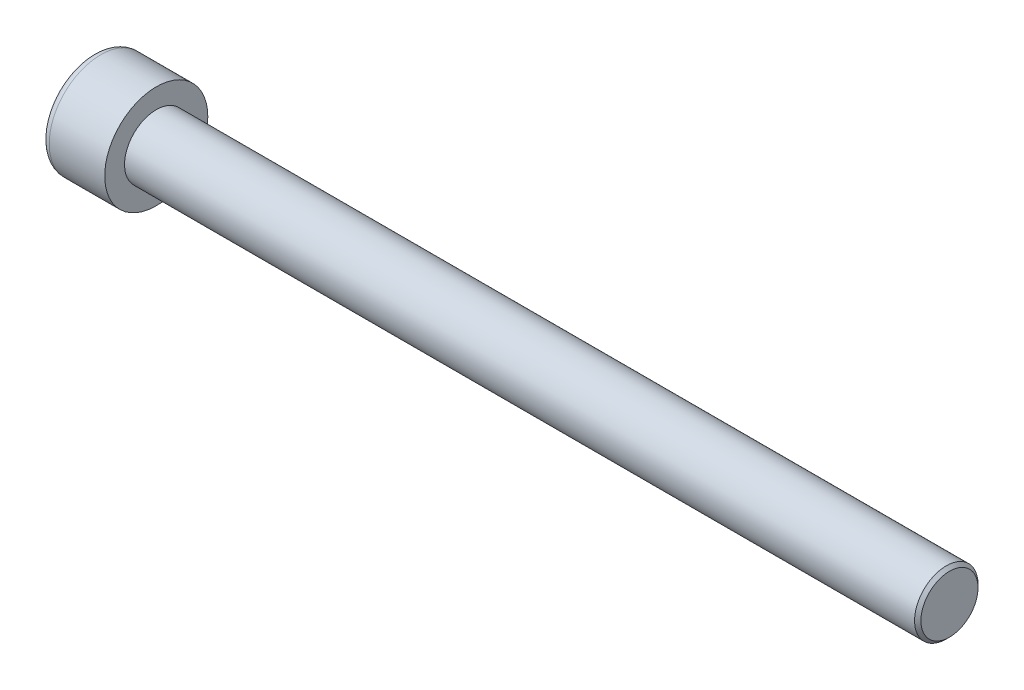
SolidWorks part; units mm, degrees
ref_plane "Front" through (0, 0, 0) normal (0, 0, 1) x (1, 0, 0)
ref_plane "Top" through (0, 0, 0) normal (0, 1, 0) x (1, 0, 0)
ref_plane "Right" through (0, 0, 0) normal (1, 0, 0) x (0, 0, -1)
sketch "Sketch1" plane through (0, 0, 0) normal (1, 0, 0) x (0, 0, -1)
  circle A0 centre (0, 0) radius 6.5
  dimension "dk" = 13
extrude "BaseHead" add sketch "Sketch1" along normal blind 8
sketch "Sketch2" plane through (8, 0, 0) normal (1, 0, 0) x (0, 0, -1)
  circle A0 centre (0, 0) radius 4
  dimension "d" = 8
extrude "BaseBody" add sketch "Sketch2" along normal blind 100
cosmetic thread "ThreadCosmetic1" [suppressed] parameters "b"=12, "D2"=6.647
sketch "Sketch3" plane through (0, 0, 0) normal (1, 0, 0) x (0, 0, -1)
  line L1 (3.4641, 0) -> (1.7321, 3)
  line L2 (1.7321, 3) -> (-1.7321, 3)
  line L3 (-1.7321, 3) -> (-3.4641, 0)
  line L4 (-3.4641, 0) -> (-1.7321, -3)
  line L5 (-1.7321, -3) -> (1.7321, -3)
  line L6 (1.7321, -3) -> (3.4641, 0)
  circle A0 centre (0, 0) radius 3 construction
  dimension "s" = 6
  dimension "e" = 6.9282
extrude "HexagonSocket" cut sketch "Sketch3" along normal blind 4
sketch "Sketch4" plane through (-4.1961, 0.75, 0) normal (0, 0, 1) x (-1, 0, 0)
  line L0 (-8.1961, 3.75) -> (-9.9282, 0.75)
  line L2 (-9.9282, 0.75) -> (-8.1961, 0.75)
  line L3 (-8.1961, 0.75) -> (-8.1961, 3.75)
  line L4 (-5.0351, 0.75) -> (0.839, 0.75) construction
  line L5 (-112.1961, 0.75) -> (-12.1961, 0.75) construction
  line L6 (-12.1961, 0.75) -> (-4.1961, 0.75) construction
  dimension "m" = 60
revolve "Cut-Revolve1" cut sketch "Sketch4" angle 360 about L4
fillet "HeadFillet" [suppressed] radius 0.4
fillet "TopFillet" radius 1 1 edges at (0, 0, -6.5)
chamfer "Chamfer1" distance 0.4 angle 45 1 edges at (108, 0, -4)
sketch "Sketch5" plane through (0, 0, 0) normal (0, 0, 1) x (1, 0, 0)
  line L0 (107.6, 3.4141) -> (107.9383, 4)
  line L1 (107.9383, 4) -> (107.9383, 4.6765)
  line L2 (107.9383, 4.6765) -> (107.2618, 4.6765)
  line L3 (107.2618, 4.6765) -> (107.2618, 4)
  line L4 (107.2618, 4) -> (107.6, 3.4141)
  line L5 (0, 0) -> (7.8886, 0) construction
  line L6 (107.6, -4) -> (107.6, 4) construction
  dimension "D1" = 8
  dimension "D2" = 0.6765
revolve "Cut-Revolve10" [suppressed] cut sketch "Sketch5" angle 360 about L5
pattern_linear "LPattern10" [suppressed] count 15 spacing 0.8118 along (1, 0, 0)
equation "\"r1@TopFillet\" = \"d@Sketch2\" / 8"
equation "\"D1@Chamfer1\" = \"r@HeadFillet\""
equation "\"D1@Sketch5\" = \"d@Sketch2\""
equation "\"D2@Sketch5\" =  ( \"d@Sketch2\" - \"D2@ThreadCosmetic1\" )  / 2"
equation "\"D3@LPattern10\" = \"D2@Sketch5\" * 1.2"
equation "\"D1@LPattern10\" = \"b@ThreadCosmetic1\" / \"D3@LPattern10\""
